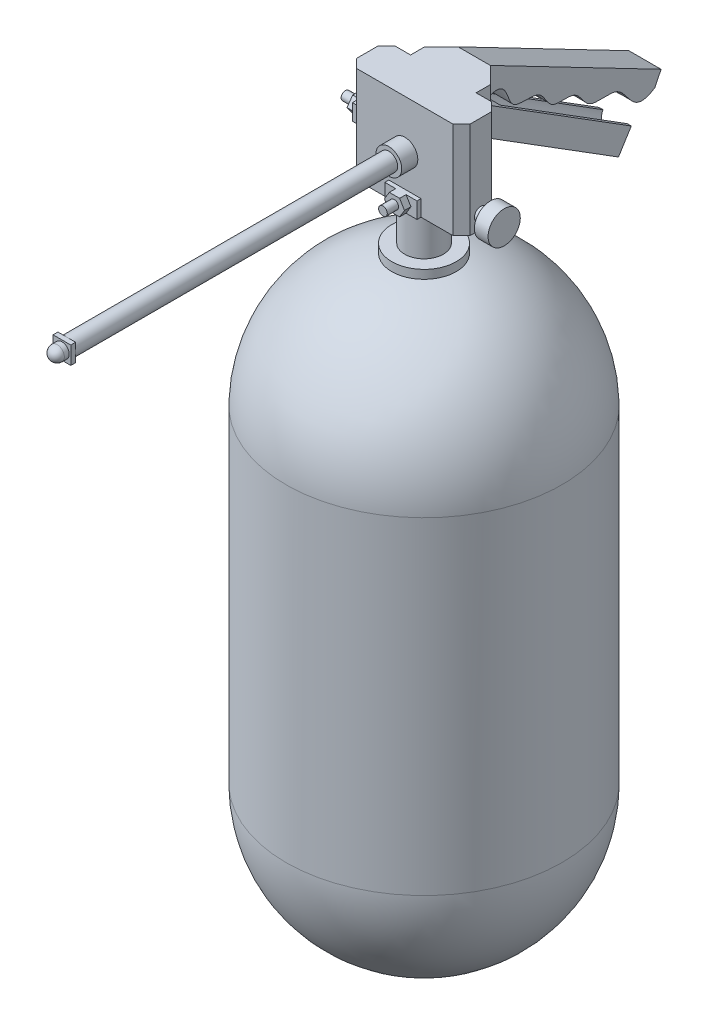
SolidWorks part; units mm, degrees
ref_plane "Front Plane" through (0, 0, 0) normal (0, 0, 1) x (1, 0, 0)
ref_plane "Top Plane" through (0, 0, 0) normal (0, 1, 0) x (1, 0, 0)
ref_plane "Right Plane" through (0, 0, 0) normal (1, 0, 0) x (0, 0, -1)
sketch "Sketch1" plane through (0, 0, 0) normal (0, 1, 0) x (1, 0, 0)
  circle A0 centre (0, 0) radius 85.725
extrude "Boss-Extrude1" add sketch "Sketch1" along normal blind 203.2
sketch3d "3DSketch5"
  line L1 (0, 313.8574, 0) -> (0, -39.2248, 0) construction
  line L2 (0, 201.578, 0) -> (-85.725, 203.2, 0)
  arc A0 (0, 287.3184, 0) -> (-85.725, 203.2, 0) centre (0, 201.578, 0) ccw
  circle A2 centre (0, 203.2, 0) radius 85.725 construction
  point P3 (0, 201.578, 85.7403)
  point P7 (0, 288.925, 0)
sketch "Sketch28" plane through (0, 0, 0) normal (0, 0, 1) x (1, 0, 0)
  line L0 (0, 287.3184) -> (0, 201.578)
  line L1 (-85.725, 203.2) -> (0, 201.578)
  arc A0 (0, 287.3184) -> (-85.725, 203.2) centre (0, 201.578) ccw
revolve "Revolve1" add sketch "Sketch28" angle 360 about L1
sketch "Sketch29" plane through (0, 0, 0) normal (0, 0, 1) x (1, 0, 0)
  line L0 (0, 0) -> (0, -85.725)
  line L1 (85.725, 0) -> (0, 0)
  arc A0 (0, -85.725) -> (85.725, 0) centre (0, 0) ccw
revolve "Revolve2" add sketch "Sketch29" angle 360 about L1
ref_plane "Plane1" through (0, 287.3184, 0) normal (0, 1, 0) x (1, 0, 0)
sketch "Sketch31" plane through (0, 287.3184, 0) normal (0, 1, 0) x (1, 0, 0)
  circle A0 centre (0, 0) radius 20
extrude "Boss-Extrude2" add sketch "Sketch31" along normal blind 3 and the other way blind 3
sketch "Sketch32" plane through (0, 290.3184, 0) normal (0, 1, 0) x (1, 0, 0)
  circle A0 centre (0, 0) radius 12
extrude "Boss-Extrude3" add sketch "Sketch32" along normal blind 25 contours A0
sketch "Sketch33" plane through (0, 315.3184, 0) normal (0, 1, 0) x (1, 0, 0)
  line L0 (30, 12) -> (-30, 12)
  line L1 (30, 12) -> (35.2894, 6.7106)
  line L2 (0, 27.9717) -> (0, -27.4313) construction
  line L3 (56.5554, 0) -> (-34.5278, 0) construction
  line L4 (0, 0) -> (-85.725, 0) construction
  line L5 (35.2894, 6.7106) -> (35.2894, -6.7106)
  line L6 (30, -12) -> (35.2894, -6.7106)
  line L7 (30, -12) -> (-30, -12)
  line L8 (-30, -12) -> (-35.2894, -6.7106)
  line L9 (-30, 12) -> (-35.2894, 6.7106)
  line L10 (-35.2894, 6.7106) -> (-35.2894, -6.7106)
  circle A0 centre (0, 0) radius 12 construction
  circle A1 centre (0, 0) radius 12 construction
  point P16 (35.2894, 0)
  point P20 (0, -12)
  point P22 (0, 12)
extrude "Boss-Extrude6" add sketch "Sketch33" along normal blind 60
sketch "Sketch34" plane through (35.2894, 0, 0) normal (1, 0, 0) x (0, 0, -1)
  circle A0 centre (0, 323.7255) radius 4
extrude "Boss-Extrude7" add sketch "Sketch34" along normal blind 6
sketch "Sketch35" plane through (41.2894, 0, 0) normal (1, 0, 0) x (0, 0, -1)
  circle A0 centre (0, 323.7255) radius 10
extrude "Boss-Extrude8" add sketch "Sketch35" along normal blind 8.5
sketch "Sketch36" plane through (0, 0, 12) normal (0, 0, 1) x (1, 0, 0)
  line L0 (10.144, 315.3184) -> (10.144, 325.3184)
  line L1 (0, 315.3184) -> (30, 315.3184) construction
  line L2 (10.144, 315.3184) -> (-9.856, 315.3184)
  line L4 (-30, 315.3184) -> (0, 315.3184) construction
  line L5 (10.144, 325.3184) -> (-9.856, 325.3184)
  line L6 (-9.856, 325.3184) -> (-9.856, 315.3184)
extrude "Boss-Extrude9" add sketch "Sketch36" along normal blind 2.5
sketch "Sketch37" plane through (0, 0, 14.5) normal (0, 0, 1) x (1, 0, 0)
  line L0 (0.144, 325.3184) -> (3.344, 325.3184)
  line L2 (0.144, 325.3184) -> (-3.056, 325.3184)
  line L3 (-3.056, 325.3184) -> (-6.0984, 320.3184)
  line L4 (-6.0984, 320.3184) -> (-3.056, 315.3184)
  line L5 (10.144, 325.3184) -> (-9.856, 325.3184) construction
  line L6 (10.144, 325.3184) -> (-9.856, 325.3184) construction
  line L7 (-12, 315.3184) -> (12, 315.3184) construction
  line L8 (-3.056, 315.3184) -> (3.344, 315.3184)
  line L9 (-9.856, 315.3184) -> (10.144, 315.3184) construction
  line L11 (3.344, 325.3184) -> (6.3864, 320.3184)
  line L13 (6.3864, 320.3184) -> (3.344, 315.3184)
extrude "Boss-Extrude10" add sketch "Sketch37" along normal blind 4
sketch "Sketch38" plane through (0, 0, 18.5) normal (0, 0, 1) x (1, 0, 0)
  circle A0 centre (0, 320.3184) radius 2.7
extrude "Boss-Extrude11" add sketch "Sketch38" along normal blind 7
sketch "Sketch39" plane through (-35.2894, 0, 0) normal (-1, 0, 0) x (0, 0, 1)
  line L0 (6.7106, 350.3184) -> (-6.7106, 350.3184)
  line L1 (6.7106, 375.3184) -> (6.7106, 315.3184) construction
  line L2 (6.7106, 340.3184) -> (6.7106, 350.3184)
  line L3 (-6.7106, 375.3184) -> (-6.7106, 315.3184) construction
  line L4 (-6.7106, 350.3184) -> (-6.7106, 340.3184)
  line L5 (-6.7106, 340.3184) -> (6.7106, 340.3184)
extrude "Boss-Extrude12" add sketch "Sketch39" along normal blind 2.5
sketch "Sketch40" plane through (-37.7894, 0, 0) normal (-1, 0, 0) x (0, 0, 1)
  line L1 (2.5, 350.3184) -> (6.0389, 345.3184)
  line L2 (6.7106, 350.3184) -> (-6.7106, 350.3184) construction
  line L4 (-2.5, 350.3184) -> (2.5, 350.3184)
  line L5 (6.0389, 345.3184) -> (2.5, 340.3184)
  line L6 (-6.7106, 340.3184) -> (6.7106, 340.3184) construction
  line L8 (2.5, 340.3184) -> (-2.5, 340.3184)
  line L9 (-6.7106, 340.3184) -> (6.7106, 340.3184) construction
  line L10 (0, 350.3184) -> (0, 340.0754) construction
  line L11 (-6.0389, 345.3184) -> (-2.5, 340.3184)
  line L12 (-2.5, 350.3184) -> (-6.0389, 345.3184)
extrude "Boss-Extrude13" add sketch "Sketch40" along normal blind 4
sketch "Sketch41" plane through (-41.7894, 0, 0) normal (-1, 0, 0) x (0, 0, 1)
  circle A0 centre (0, 345.3184) radius 2.7
extrude "Boss-Extrude14" add sketch "Sketch41" along normal blind 7
sketch "Sketch42" plane through (0, 0, 12) normal (0, 0, 1) x (1, 0, 0)
  circle A0 centre (0.144, 345.3184) radius 8
extrude "Boss-Extrude15" add sketch "Sketch42" along normal blind 10
sketch "Sketch43" plane through (0, 0, 22) normal (0, 0, 1) x (1, 0, 0)
  circle A0 centre (0.144, 345.3184) radius 5.5
extrude "Boss-Extrude16" add sketch "Sketch43" along normal blind 200
sketch "Sketch44" plane through (0, 0, 222) normal (0, 0, 1) x (1, 0, 0)
  line L4 (5.644, 339.8184) -> (-5.356, 339.8184)
  line L5 (-5.356, 339.8184) -> (-5.356, 350.8184)
  line L6 (-5.356, 350.8184) -> (5.644, 350.8184)
  line L7 (5.644, 350.8184) -> (5.644, 339.8184)
extrude "Boss-Extrude17" add sketch "Sketch44" along normal blind 3
sketch "Sketch45" plane through (0, 0, 225) normal (0, 0, 1) x (1, 0, 0)
  circle A0 centre (0.144, 345.3184) radius 4.5
extrude "Boss-Extrude18" add sketch "Sketch45" along normal blind 3
sketch "Sketch47" plane through (0, 0, 228) normal (0, 0, 1) x (1, 0, 0)
  line L0 (0.144, 349.8184) -> (0.144, 340.8184) construction
  circle A0 centre (0.144, 345.3184) radius 4.5 construction
revolve "Revolve3" add sketch "Sketch47" angle 180 about L0
sketch "Sketch48" plane through (0, 375.3184, 0) normal (0, 1, 0) x (1, 0, 0)
  line L0 (-20.3579, -12) -> (-20.3579, 20.8202)
  line L1 (-30, -12) -> (30, -12) construction
  line L3 (0, -12) -> (0, 39.6745) construction
  line L4 (-20.3579, 20.8202) -> (-10.039, 31.1391)
  line L5 (-10.039, 31.1391) -> (10.039, 31.1391)
  line L6 (20.3579, -12) -> (20.3579, 20.8202)
  line L7 (20.3579, 20.8202) -> (10.039, 31.1391)
  line L8 (20.3579, -12) -> (-20.3579, -12)
  point P12 (0, 31.1391)
extrude "Boss-Extrude19" add sketch "Sketch48" against normal blind 16
ref_plane "Plane3" through (10.039, 0, 0) normal (-1, 0, 0) x (0, 0, 1)
sketch "Sketch52" plane through (10.039, 0, 0) normal (-1, 0, 0) x (0, 0, 1)
  line L0 (-31.1391, 375.3184) -> (-137.1985, 320.2163)
  line L1 (-137.1985, 320.2163) -> (-133.3303, 312.2903)
  line L2 (-31.1391, 375.3184) -> (-31.1391, 359.3184)
  spline S0 degree 3 poles (-31.1391, 359.3184) (-42.3798, 363.1584) (-39.5917, 340.8187) (-62.8888, 349.0991) (-67.9269, 331.0532) (-84.9807, 337.1463) (-91.5296, 319.1055) (-116.3524, 328.6844) (-119.1165, 302.8083) (-133.3303, 312.2903) knots 0 0 0 0 0.166178 0.30482 0.403837 0.523806 0.628724 0.776597 1 1 1 1
extrude "Boss-Extrude20" add sketch "Sketch52" along normal blind 20
sketch "Sketch53" plane through (10.039, 0, 0) normal (-1, 0, 0) x (0, 0, 1)
  line L0 (-25.9796, 359.3184) -> (-25.9796, 339.3184)
  line L1 (-20.8202, 359.3184) -> (-31.1391, 359.3184) construction
  line L2 (-25.9796, 339.3184) -> (-110.7377, 286.2518)
  line L3 (-110.7377, 286.2518) -> (-118.6977, 298.9655)
  line L4 (-118.6977, 298.9655) -> (-31.1391, 353.7855)
  line L5 (-31.1391, 353.7855) -> (-31.1391, 359.3184)
  line L6 (-31.1391, 359.3184) -> (-25.9796, 359.3184)
extrude "Boss-Extrude21" add sketch "Sketch53" along normal blind 20
sketch "Sketch55" plane through (0, 30.8024, 49.1977) normal (0, -0.5307, -0.8476) x (-1, 0, 0)
  line L3 (7.5, 316.3863) -> (-7.5, 316.3863)
  arc A1 (-7.5, 316.3863) -> (7.5, 316.3863) centre (0, 316.3863) ccw
extrude "Cut-Extrude2" cut sketch "Sketch55" against normal blind 93
